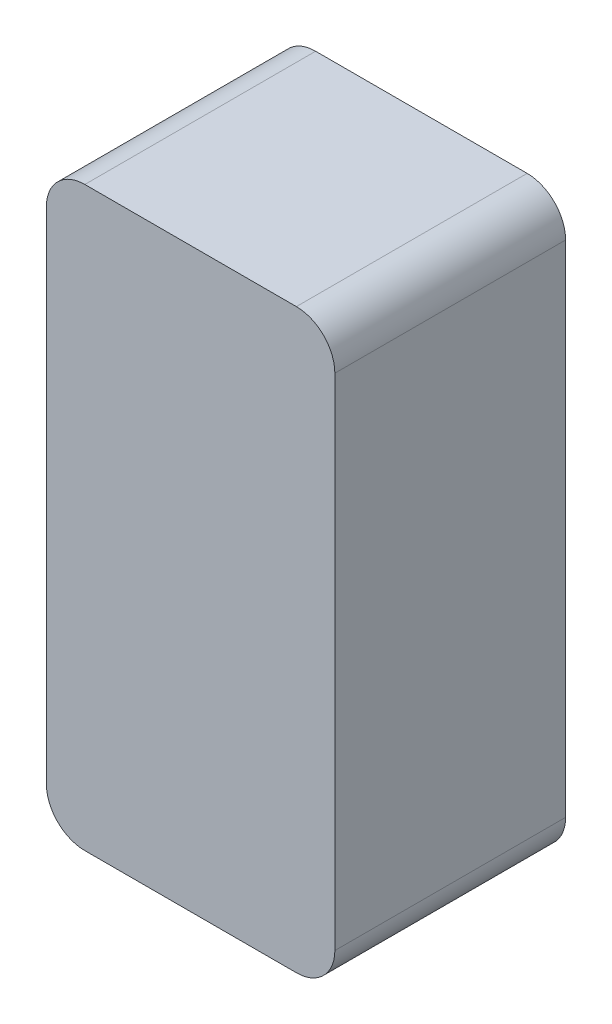
SolidWorks part; units mm, degrees
ref_plane "Front Plane" through (0, 0, 0) normal (0, 0, 1) x (1, 0, 0)
ref_plane "Top Plane" through (0, 0, 0) normal (0, 1, 0) x (1, 0, 0)
ref_plane "Right Plane" through (0, 0, 0) normal (1, 0, 0) x (0, 0, -1)
sketch "Sketch1" plane through (0, 0, 0) normal (0, 0, 1) x (1, 0, 0)
  line L1 (-7.5, 15) -> (7.5, 15)
  line L2 (-7.5, 15) -> (-7.5, -15)
  line L3 (-7.5, -15) -> (7.5, -15)
  line L4 (7.5, 15) -> (7.5, -15)
  line L5 (-6, 13.5) -> (6, 13.5)
  line L6 (-6, 13.5) -> (-6, -13.5)
  line L7 (-6, -13.5) -> (6, -13.5)
  line L8 (6, 13.5) -> (6, -13.5)
  dimension "D1" = 1.5
  dimension "D2" = 1.5
  dimension "D3" = 1.5
  dimension "D4" = 1.5
extrude "Boss-Extrude1" add sketch "Sketch1" along normal blind 10
sketch "Sketch2" plane through (0, -13.5, 0) normal (0, 1, 0) x (1, 0, 0)
  line L2 (-7.5, -10) -> (7.5, -10)
  line L3 (-7.5, -10) -> (-7.5, -12)
  line L4 (-7.5, -12) -> (7.5, -12)
  line L5 (7.5, -10) -> (7.5, -12)
  dimension "D1" = 2
extrude "Boss-Extrude2" add sketch "Sketch2" along normal up to surface and the other way up to surface up to face at (0, 15, 5) other way up to face at (0, -15, 5)
sketch "Sketch3" plane through (0, -15, 0) normal (0, -1, 0) x (1, 0, 0)
  line L0 (7.5, 12) -> (-7.5, -2) construction
  line L1 (-7.5, -2) -> (-7.5, 12) construction
  line L2 (-7.5, 12) -> (7.5, -2) construction
  circle A0 centre (0, 5) radius 4.953
extrude "Cut-Extrude2" cut sketch "Sketch3" against normal blind 10
fillet "Fillet1" radius 2 4 edges at (7.5, 15, 6) (-7.5, -15, 6) (7.5, -15, 6) (-7.5, 15, 6)
